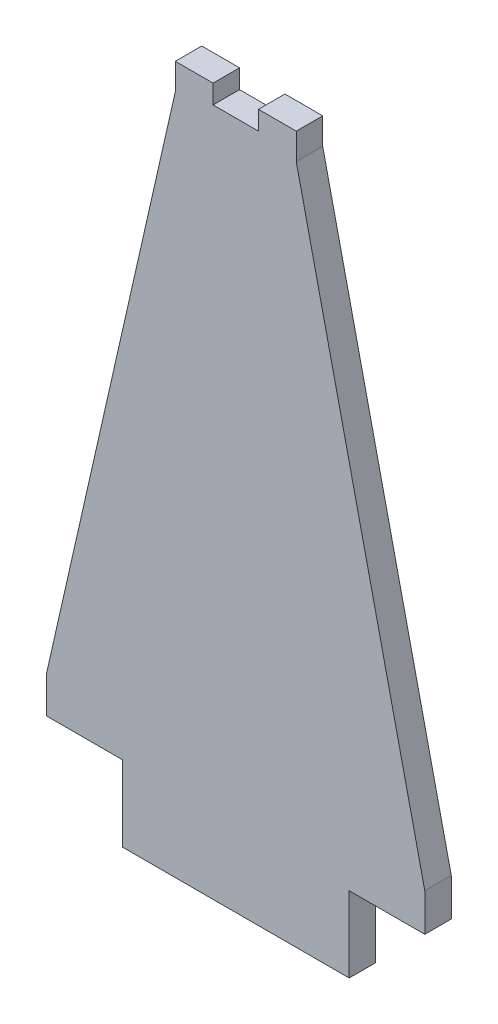
SolidWorks part; units mm, degrees
material "PBT General Purpose"
ref_plane "Front Plane" through (0, 0, 0) normal (0, 0, 1) x (1, 0, 0)
ref_plane "Top Plane" through (0, 0, 0) normal (0, 1, 0) x (1, 0, 0)
ref_plane "Right Plane" through (0, 0, 0) normal (1, 0, 0) x (0, 0, -1)
sketch "frame_outline" plane through (0, 0, 0) normal (0, 0, 1) x (1, 0, 0)
  line L110 (0, 0) -> (3, 0)
  line L117 (3, 0) -> (3, 1)
  line L118 (3, 1) -> (4, 1)
  line L119 (4, 1) -> (4, 1.5)
  line L120 (4, 1.5) -> (2.3, 9)
  line L121 (2.3, 9) -> (2.3, 9.35)
  line L122 (2.3, 9.35) -> (1.8, 9.35)
  line L123 (1.8, 9.35) -> (1.8, 9.1)
  line L124 (1.8, 9.1) -> (1.2, 9.1)
  line L125 (1.2, 9.1) -> (1.2, 9.35)
  line L126 (1.2, 9.35) -> (0.7, 9.35)
  line L127 (0.7, 9.35) -> (0.7, 9)
  line L128 (0.7, 9) -> (-1, 1.5)
  line L129 (-1, 1.5) -> (-1, 1)
  line L130 (-1, 1) -> (0, 1)
  line L131 (0, 1) -> (0, 0)
  line L132 (1.5, 9.1) -> (1.5, 0) construction
  dimension "D1" = 5
  dimension "D2" = 3
  dimension "D3" = 1
  dimension "D4" = 0.5
  dimension "D5" = 8
  dimension "D6" = 0.6
  dimension "D7" = 0.25
  dimension "D8" = 0.5
  dimension "D9" = 0.1
extrude "Boss-Extrude1" add sketch "frame_outline" along normal mid plane 0.35
equation "\"t\"= 0.25'thickness of the sheets"
equation "\"t_cf\"= 0.115'thickness of single carbon fiber layer"
equation "\"t_kapton\"= 0.025'thickness of single Kapton flex layer"
equation "\"t_fr4\"= 0.1'thickness of FR4 with copper layer"
equation "\"joint_flex\"= 0.1'Width of flextures gap"
equation "\"joint_flex_eff\"= 0.02'Width of flecture after castelation"
equation "\"joint_fold\"= 0.2'Width of folding joints for 90deg fold"
equation "\"gap_tolerance\"= 0.002'Width to have interfecence fit between carbon fiber inserts"
equation "\"assemble_angle\"= 90'Angle of assembly parts"
equation "\"D1@Boss-Extrude1\"=0.35"
equation "\"link_lift\"= 0.5'Actuation linkage amplification for the lift motion"
equation "\"link_swing\"= 0.45'Actuation linkage amplification for the swing motion"
